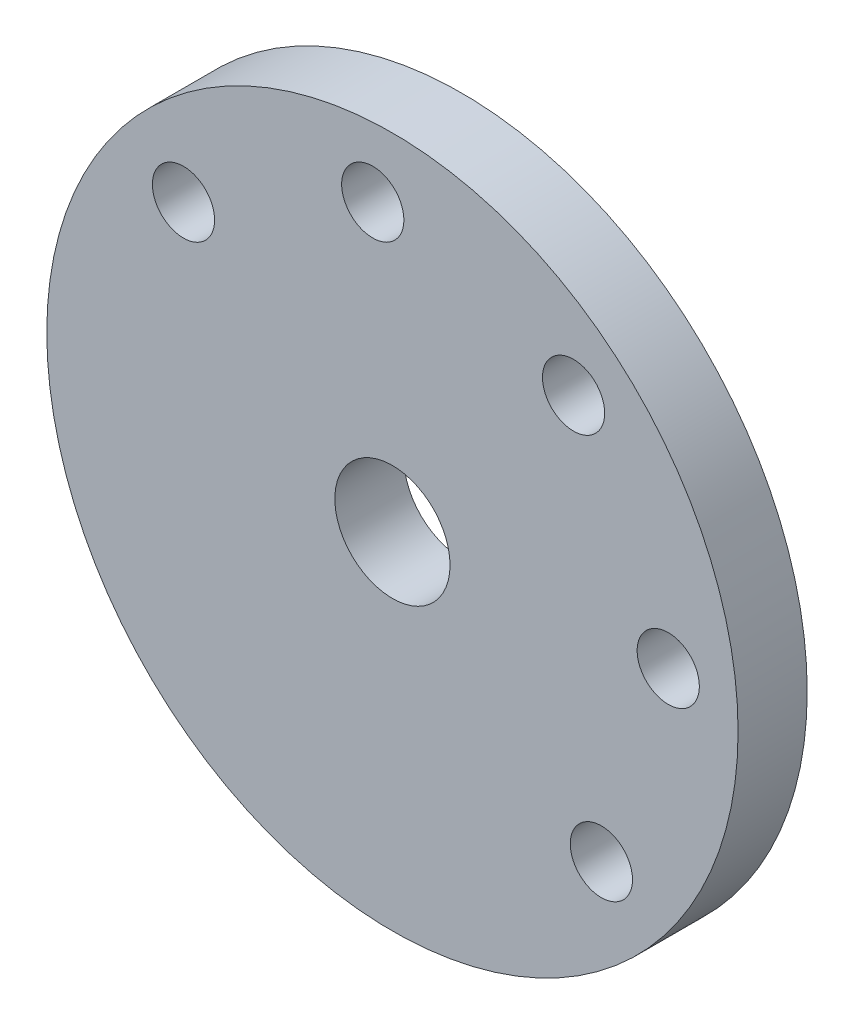
SolidWorks part; units mm, degrees
ref_plane "前视基准面" through (0, 0, 0) normal (0, 0, 1) x (1, 0, 0)
ref_plane "上视基准面" through (0, 0, 0) normal (0, 1, 0) x (1, 0, 0)
ref_plane "右视基准面" through (0, 0, 0) normal (1, 0, 0) x (0, 0, -1)
other "Configuration Table"
sketch "草图1" plane through (0, 0, 0) normal (0, 0, 1) x (1, 0, 0)
  circle A0 centre (125, 0) radius 15
  circle A4 centre (132.8601, 9.0674) radius 1.35
  circle A5 centre (136.9696, 0.8537) radius 1.35
  circle A6 centre (134.0674, -7.8601) radius 1.35
  circle A9 centre (124.1463, 11.9696) radius 1.35
  circle A10 centre (115.9326, 7.8601) radius 1.35
  circle A12 centre (125, 0) radius 2.5
  dimension "D1" = 30
extrude "凸台-拉伸1" add sketch "草图1" along normal blind 3
